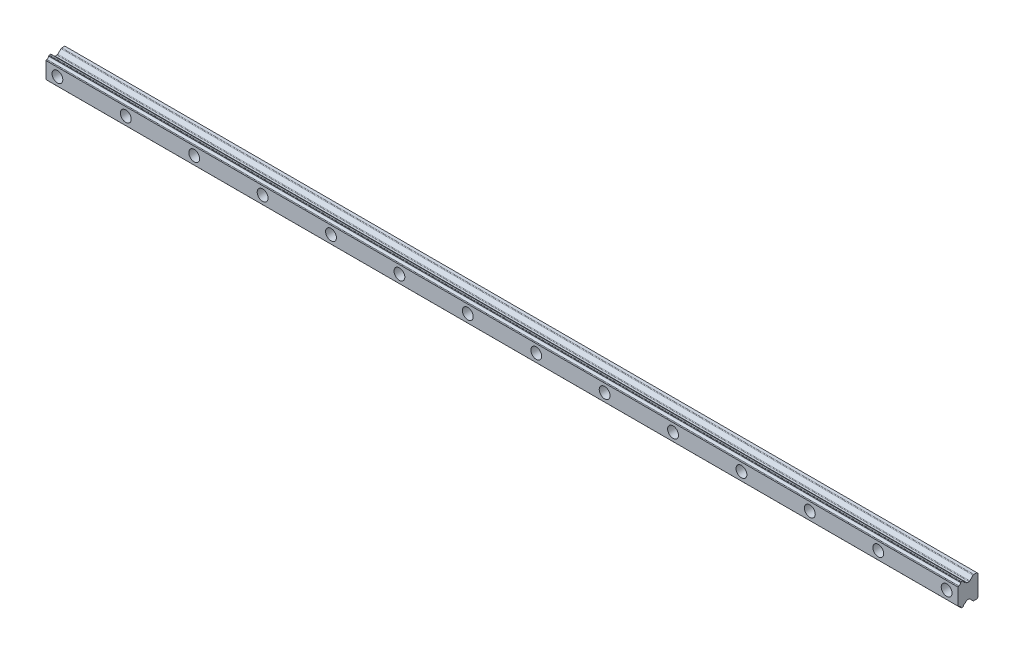
SolidWorks part; units mm, degrees
material "1.0037 (S235JR)"
ref_plane "Front Plane" through (0, 0, 0) normal (0, 0, 1) x (1, 0, 0)
ref_plane "Top Plane" through (0, 0, 0) normal (0, 1, 0) x (1, 0, 0)
ref_plane "Right Plane" through (0, 0, 0) normal (1, 0, 0) x (0, 0, -1)
sketch3d "3DSketch1"
  line L0 (0, 0, 0) -> (-800, 0, 0)
  dimension "D1" = 800
ref_plane "Plane1" through (0, 0, 0) normal (-1, 0, 0) x (0, -0.7071, 0.7071)
other "Hgr HGR20(1)"
ref_plane "Plane3" through (0, 0, 0) normal (-1, 0, 0) x (0, -1, 0)
sketch "Sketch14" plane through (0, 0, 0) normal (-1, 0, 0) x (0, -1, 0)
  line L0 (-9, 0) -> (9, 0)
  line L1 (9, 0) -> (10, 1)
  line L2 (10, 1) -> (10, 3.6565)
  line L3 (9.7071, 4.3636) -> (6.8929, 7.1778)
  line L4 (6.6, 7.8849) -> (6.6, 9.4451)
  line L5 (6.8929, 10.1522) -> (7.6302, 10.8894)
  line L6 (9.6906, 12.9499) -> (9.8536, 13.1128)
  line L7 (10, 13.4664) -> (10, 14.5236)
  line L8 (9.8536, 14.8772) -> (9.6785, 15.0522)
  line L9 (7.6325, 17.0982) -> (7.2307, 17.5)
  line L10 (7.2307, 17.5) -> (-7.2307, 17.5)
  line L11 (-7.2307, 17.5) -> (-7.6325, 17.0982)
  line L12 (-9.6785, 15.0522) -> (-9.8536, 14.8772)
  line L13 (-10, 14.5236) -> (-10, 13.4664)
  line L14 (-9.8536, 13.1128) -> (-9.6906, 12.9499)
  line L15 (-7.6302, 10.8894) -> (-6.8929, 10.1522)
  line L16 (-6.6, 9.4451) -> (-6.6, 7.8849)
  line L17 (-6.8929, 7.1778) -> (-9.7071, 4.3636)
  line L18 (-10, 3.6565) -> (-10, 1)
  line L19 (-10, 1) -> (-9, 0)
  arc A0 (10, 3.6565) -> (9.7071, 4.3636) centre (9, 3.6565) ccw
  arc A1 (6.6, 7.8849) -> (6.8929, 7.1778) centre (7.6, 7.8849) ccw
  arc A2 (6.8929, 10.1522) -> (6.6, 9.4451) centre (7.6, 9.4451) ccw
  arc A3 (7.6302, 10.8894) -> (7.8468, 11.2275) centre (7.3529, 11.3055) ccw
  arc A4 (9.4318, 12.8125) -> (7.8468, 11.2275) centre (9.8106, 10.8487) ccw
  arc A5 (9.4318, 12.8125) -> (9.6906, 12.9499) centre (9.3371, 13.3035) ccw
  arc A6 (9.8536, 13.1128) -> (10, 13.4664) centre (9.5, 13.4664) ccw
  arc A7 (10, 14.5236) -> (9.8536, 14.8772) centre (9.5, 14.5236) ccw
  arc A8 (9.6785, 15.0522) -> (9.422, 15.1892) centre (9.3249, 14.6987) ccw
  arc A9 (7.8482, 16.763) -> (9.422, 15.1892) centre (9.8101, 17.1511) ccw
  arc A10 (7.8482, 16.763) -> (7.6325, 17.0982) centre (7.3547, 16.6825) ccw
  arc A11 (-7.6325, 17.0982) -> (-7.8482, 16.763) centre (-7.3547, 16.6825) ccw
  arc A12 (-9.422, 15.1892) -> (-7.8482, 16.763) centre (-9.8101, 17.1511) ccw
  arc A13 (-9.422, 15.1892) -> (-9.6785, 15.0522) centre (-9.3249, 14.6987) ccw
  arc A14 (-9.8536, 14.8772) -> (-10, 14.5236) centre (-9.5, 14.5236) ccw
  arc A15 (-10, 13.4664) -> (-9.8536, 13.1128) centre (-9.5, 13.4664) ccw
  arc A16 (-9.6906, 12.9499) -> (-9.4318, 12.8125) centre (-9.3371, 13.3035) ccw
  arc A17 (-7.8468, 11.2275) -> (-9.4318, 12.8125) centre (-9.8106, 10.8487) ccw
  arc A18 (-7.8468, 11.2275) -> (-7.6302, 10.8894) centre (-7.3529, 11.3055) ccw
  arc A19 (-6.6, 9.4451) -> (-6.8929, 10.1522) centre (-7.6, 9.4451) ccw
  arc A20 (-6.8929, 7.1778) -> (-6.6, 7.8849) centre (-7.6, 7.8849) ccw
  arc A21 (-9.7071, 4.3636) -> (-10, 3.6565) centre (-9, 3.6565) ccw
  point P64 (0, 0)
hole_wizard "Hole1" positions "Sketch17" profile "Sketch18" legacy end condition up to next
sketch "Sketch17" plane through (0, 0, 17.5) normal (0, 0, 1) x (1, 0, 0)
  line L1 (-790, 0) -> (-10, 0)
  line L2 (-800, -7.2307) -> (-800, 7.2307) construction
  point P5 (-10, 0)
  dimension "D1" = 10
  dimension "D2" = 10
sketch "Sketch18" plane through (-10, 0, 17.5) normal (1, 0, 0) x (0, -1, 0)
  line L0 (0, 0) -> (0, 17.5)
  line L1 (0, 17.5) -> (3, 17.5)
  line L2 (3, 17.5) -> (3, 8.5)
  line L3 (3, 8.5) -> (4.75, 8.5)
  line L4 (4.75, 8.5) -> (4.75, 0)
  line L5 (4.75, 0) -> (0, 0)
  line L6 (0, 110) -> (0, -10) construction
  dimension "Diameter" = 6
  dimension "Depth" = 17.5
  dimension "C-Bore Diameter" = 9.5
  dimension "C-Bore Depth" = 8.5
pattern_curve "CrvPattern1" of "Hole1" parameters "D1"=14, "D3"=10, "D2"=1, "D4"=10
